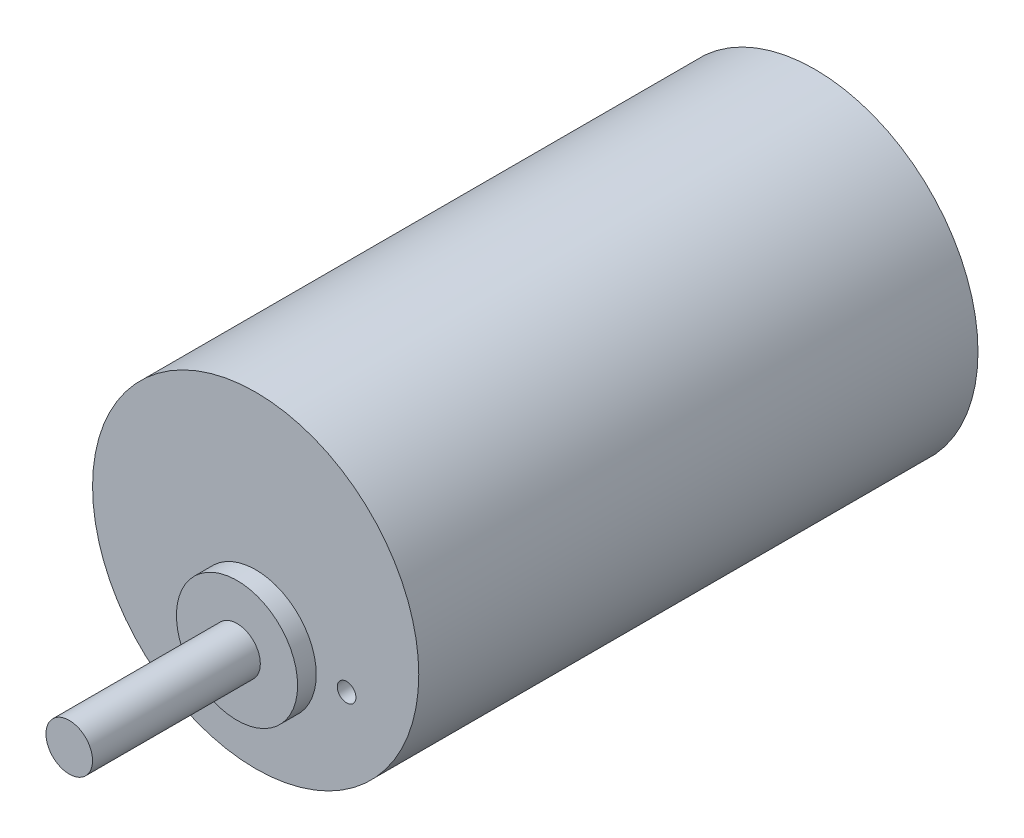
SolidWorks part; units mm, degrees
ref_plane "Front Plane" through (0, 0, 0) normal (0, 0, 1) x (1, 0, 0)
ref_plane "Top Plane" through (0, 0, 0) normal (0, 1, 0) x (1, 0, 0)
ref_plane "Right Plane" through (0, 0, 0) normal (1, 0, 0) x (0, 0, -1)
sketch "Sketch1" plane through (0, 0, 0) normal (0, 0, 1) x (1, 0, 0)
  circle A0 centre (0, 0) radius 17.5
  dimension "D1" = 35
extrude "Motor-Base" add sketch "Sketch1" along normal blind 60
sketch "Sketch2" plane through (0, 0, 60) normal (0, 0, 1) x (1, 0, 0)
  line L0 (0, -5.5) -> (0, 17.5) construction
  circle A1 centre (0, 0) radius 17.5 construction
  circle A2 centre (0, -5.5) radius 2.5
  dimension "D1" = 5
  dimension "D2" = 23
extrude "Shaft" add sketch "Sketch2" along normal blind 20
sketch "Sketch3" plane through (0, 0, 60) normal (0, 0, 1) x (1, 0, 0)
  circle A0 centre (0, -5.5) radius 6.5
  dimension "D1" = 13
extrude "Boss-Extrude3" add sketch "Sketch3" along normal blind 2
sketch "Sketch4" plane through (0, 0, 60) normal (0, 0, 1) x (1, 0, 0)
  line L0 (0, -5.5) -> (0, -17.5) construction
  line L1 (0, -5.5) -> (16.6132, -5.5) construction
  circle A0 centre (0, 0) radius 17.5 construction
  circle A1 centre (9.7596, -5.5) radius 1
extrude "Cut-Extrude1" cut sketch "Sketch4" against normal blind 2.54
